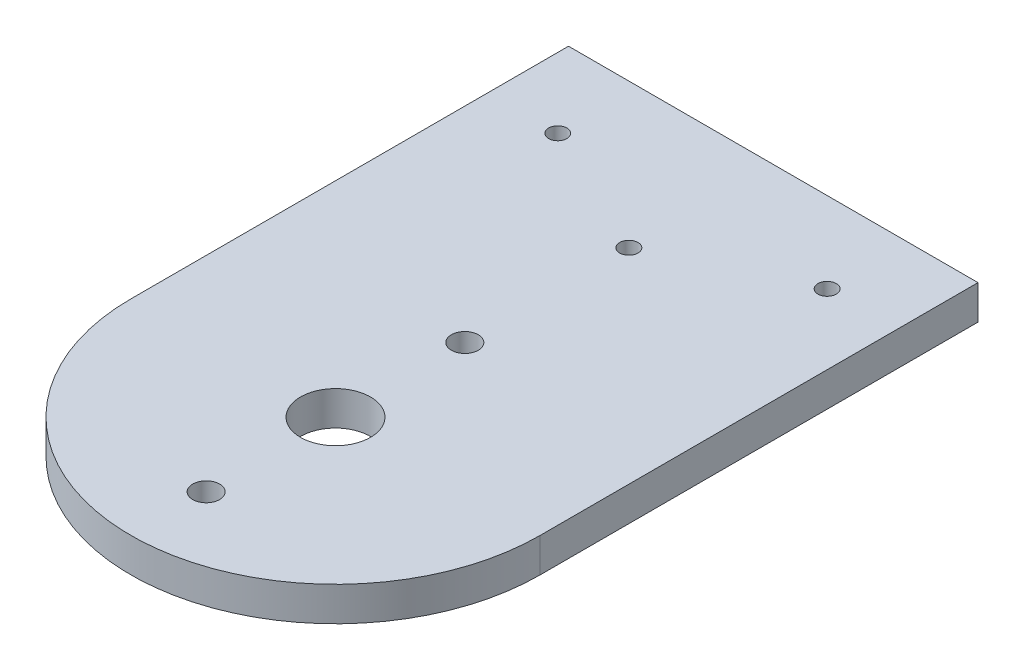
SolidWorks part; units mm, degrees
material "Aleación 6061"
ref_plane "Alzado" through (0, 0, 0) normal (0, 0, 1) x (1, 0, 0)
ref_plane "Planta" through (0, 0, 0) normal (0, 1, 0) x (1, 0, 0)
ref_plane "Vista lateral" through (0, 0, 0) normal (1, 0, 0) x (0, 0, -1)
sketch "Croquis1" plane through (0, 0, 0) normal (0, 1, 0) x (1, 0, 0)
  line L1 (-38, -90.2) -> (38, -90.2)
  line L2 (-38, -90.2) -> (-38, -171.45)
  line L3 (-38, -171.45) -> (38, -171.45)
  line L4 (38, -90.2) -> (38, -171.45)
  dimension "D1" = 38
  dimension "D2" = 90.2
  dimension "D3" = 38
  dimension "D4" = 90.2
  dimension "D5" = 38
  dimension "D6" = 171.45
  dimension "D7" = 38
  dimension "D8" = 171.45
extrude "Pared_B_chumacera_J2" add sketch "Croquis1" along normal blind 6.35 from offset 21.35
sketch "Croquis2" plane through (0, 0, 0) normal (0, 1, 0) x (1, 0, 0)
  circle A0 centre (0, -171.45) radius 38
  dimension "D1" = 76
  dimension "D2" = 171.45
extrude "Pared_B_chumacera_J2_redondeo" add sketch "Croquis2" along normal blind 6.35 from offset 21.35
sketch "Croquis3" plane through (0, 0, 0) normal (0, 1, 0) x (1, 0, 0)
  circle A0 centre (0, -171.45) radius 6.5
  circle A1 centre (0, -195.45) radius 2.5
  circle A2 centre (0, -147.45) radius 2.5
  dimension "D1" = 13
  dimension "D2" = 5
  dimension "D3" = 5
  dimension "D4" = 171.45
  dimension "D5" = 195.45
  dimension "D6" = 147.45
extrude "Paso_perno_y_rosca_M6_KFL001" cut sketch "Croquis3" along normal blind 6.35 from offset 21.35
sketch "Croquis4" plane through (0, 0, 0) normal (0, 1, 0) x (1, 0, 0)
  circle A0 centre (-25, -105.2) radius 1.25
  circle A1 centre (25, -105.2) radius 1.25
  dimension "D1" = 2.5
  dimension "D2" = 2.5
  dimension "D3" = 25
  dimension "D4" = 105.2
  dimension "D5" = 25
  dimension "D6" = 105.2
extrude "Rosca_M3_escuadras" cut sketch "Croquis4" along normal blind 6.35 from offset 21.35
sketch "Croquis5" plane through (0, 0, 0) normal (0, 0, 1) x (1, 0, 0)
  circle A0 centre (-30, -18.175) radius 2
  circle A1 centre (30, -18.175) radius 2
  dimension "D1" = 4
  dimension "D2" = 4
  dimension "D3" = 30
  dimension "D4" = 18.175
  dimension "D5" = 30
  dimension "D6" = 18.175
extrude "Pasadores_D4" cut sketch "Croquis5" along normal blind 8 from offset 90.2
sketch "Croquis6" plane through (0, 0, 0) normal (0, 1, 0) x (1, 0, 0)
  circle A0 centre (0, -117) radius 1.25
  dimension "D1" = 2.5
  dimension "D2" = 117
extrude "Rosca_M3_bases_cincho" cut sketch "Croquis6" along normal blind 6.35 from offset 21.35
sketch "Croquis7" plane through (0, 0, 0) normal (0, 1, 0) x (1, 0, 0)
  circle A0 centre (-25, -105.2) radius 1.7
  circle A1 centre (25, -105.2) radius 1.7
  dimension "D1" = 3.4
  dimension "D2" = 3.4
  dimension "D3" = 25
  dimension "D4" = 105.2
  dimension "D5" = 25
  dimension "D6" = 105.2
extrude "Paso_M3_escuadras_tuerca" cut sketch "Croquis7" along normal blind 6.35 from offset 21.35
sketch "Croquis8" plane through (0, 0, 0) normal (0, 1, 0) x (1, 0, 0)
  circle A0 centre (0, -117) radius 1.7
  dimension "D1" = 3.4
  dimension "D2" = 117
extrude "Paso_M3_base_cincho_tuerca" cut sketch "Croquis8" along normal blind 6.35 from offset 21.35
